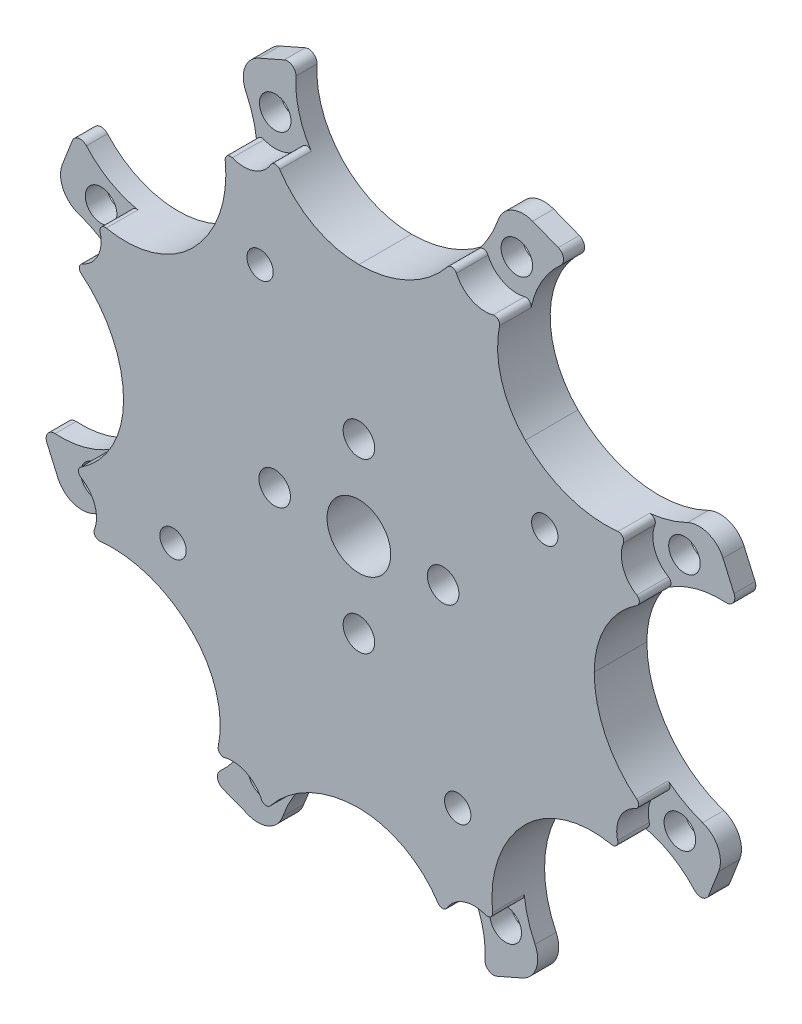
SolidWorks part; units mm, degrees
ref_plane "前视基准面" through (0, 0, 0) normal (0, 0, 1) x (1, 0, 0)
ref_plane "上视基准面" through (0, 0, 0) normal (0, 1, 0) x (1, 0, 0)
ref_plane "右视基准面" through (0, 0, 0) normal (1, 0, 0) x (0, 0, -1)
sketch "草图1" plane through (0, 0, 0) normal (0, 0, 1) x (1, 0, 0)
  line L0 (0, 31.3575) -> (0, 0) construction
  line L1 (0, 0) -> (22.1731, 22.1731) construction
  line L4 (0, 31.3575) -> (22.1731, 22.1731) construction
  line L6 (11.6409, 26.5357) -> (12.5976, 28.8454) construction
  line L7 (22.2808, 22.9688) -> (16.1797, 28.8872) construction
  line L8 (22.2808, 22.9688) -> (28.5472, 29.4288) construction
  line L9 (15.9368, 30.2296) -> (13.5034, 31.1755)
  line L10 (32.6446, 10.1066) -> (31.5928, 12.4961)
  line L11 (30.2296, -15.9368) -> (31.1755, -13.5034)
  line L12 (10.1066, -32.6446) -> (12.4961, -31.5928)
  line L13 (-15.9368, -30.2296) -> (-13.5034, -31.1755)
  line L14 (-32.6446, -10.1066) -> (-31.5928, -12.4961)
  line L15 (-30.2296, 15.9368) -> (-31.1755, 13.5034)
  line L16 (-10.1066, 32.6446) -> (-12.4961, 31.5928)
  circle A0 centre (0, 0) radius 31.3575 construction
  arc A9 (16.1797, 28.8872) -> (15.8091, 15.8091) centre (22.1731, 22.1731) ccw
  circle A13 centre (0, 0) radius 41 construction
  arc A16 (16.1797, 28.8872) -> (15.9368, 30.2296) centre (15.6469, 29.484) ccw
  arc A17 (13.5034, 31.1755) -> (10.2336, 29.6588) centre (12.5976, 28.8454) ccw
  arc A18 (0, 22.3575) -> (10.2336, 29.6588) centre (0, 33.18) ccw
  arc A19 (31.8671, 8.9856) -> (22.3575, 0) centre (31.3575, 0) ccw
  arc A20 (31.8671, 8.9856) -> (32.6446, 10.1066) centre (31.9124, 9.7843) ccw
  arc A21 (31.5928, 12.4961) -> (28.2082, 13.7357) centre (29.3046, 11.4889) ccw
  arc A22 (15.8091, 15.8091) -> (28.2082, 13.7357) centre (23.4618, 23.4618) ccw
  arc A24 (28.8872, -16.1797) -> (15.8091, -15.8091) centre (22.1731, -22.1731) ccw
  arc A25 (28.8872, -16.1797) -> (30.2296, -15.9368) centre (29.484, -15.6469) ccw
  arc A26 (31.1755, -13.5034) -> (29.6588, -10.2336) centre (28.8454, -12.5976) ccw
  arc A27 (22.3575, 0) -> (29.6588, -10.2336) centre (33.18, 0) ccw
  arc A29 (8.9856, -31.8671) -> (0, -22.3575) centre (0, -31.3575) ccw
  arc A30 (8.9856, -31.8671) -> (10.1066, -32.6446) centre (9.7843, -31.9124) ccw
  arc A31 (12.4961, -31.5928) -> (13.7357, -28.2082) centre (11.4889, -29.3046) ccw
  arc A32 (15.8091, -15.8091) -> (13.7357, -28.2082) centre (23.4618, -23.4618) ccw
  arc A34 (-16.1797, -28.8872) -> (-15.8091, -15.8091) centre (-22.1731, -22.1731) ccw
  arc A35 (-16.1797, -28.8872) -> (-15.9368, -30.2296) centre (-15.6469, -29.484) ccw
  arc A36 (-13.5034, -31.1755) -> (-10.2336, -29.6588) centre (-12.5976, -28.8454) ccw
  arc A37 (0, -22.3575) -> (-10.2336, -29.6588) centre (0, -33.18) ccw
  arc A39 (-31.8671, -8.9856) -> (-22.3575, 0) centre (-31.3575, 0) ccw
  arc A40 (-31.8671, -8.9856) -> (-32.6446, -10.1066) centre (-31.9124, -9.7843) ccw
  arc A41 (-31.5928, -12.4961) -> (-28.2082, -13.7357) centre (-29.3046, -11.4889) ccw
  arc A42 (-15.8091, -15.8091) -> (-28.2082, -13.7357) centre (-23.4618, -23.4618) ccw
  arc A44 (-28.8872, 16.1797) -> (-15.8091, 15.8091) centre (-22.1731, 22.1731) ccw
  arc A45 (-28.8872, 16.1797) -> (-30.2296, 15.9368) centre (-29.484, 15.6469) ccw
  arc A46 (-31.1755, 13.5034) -> (-29.6588, 10.2336) centre (-28.8454, 12.5976) ccw
  arc A47 (-22.3575, 0) -> (-29.6588, 10.2336) centre (-33.18, 0) ccw
  arc A49 (-8.9856, 31.8671) -> (0, 22.3575) centre (0, 31.3575) ccw
  arc A50 (-8.9856, 31.8671) -> (-10.1066, 32.6446) centre (-9.7843, 31.9124) ccw
  arc A51 (-12.4961, 31.5928) -> (-13.7357, 28.2082) centre (-11.4889, 29.3046) ccw
  arc A52 (-15.8091, 15.8091) -> (-13.7357, 28.2082) centre (-23.4618, 23.4618) ccw
  circle A54 centre (0, 0) radius 3.025
  circle A55 centre (0, 0) radius 8 construction
  circle A56 centre (-8, 0) radius 1.5
  circle A57 centre (0, 8) radius 1.5
  circle A58 centre (8, 0) radius 1.5
  circle A59 centre (0, -8) radius 1.5
  point P98 (0, 0)
  point P102 (0, 0)
  dimension "D1" = 9
  dimension "D3" = 45
  dimension "D5" = 9
  dimension "D8" = 82
  dimension "D9" = 9
  dimension "D10" = 2.5
  dimension "D11" = 0.8
  dimension "D13" = 6.05
  dimension "D14" = 16
  dimension "D15" = 3
  dimension "D2" = 24
  dimension "D6" = 11.4
  dimension "D7" = 2.5
  dimension "D17" = 8.5
  dimension "D12" = 8
  dimension "D16" = 4
extrude "凸台-拉伸1" add sketch "草图1" along normal blind 5
sketch "草图2" plane through (0, 0, 5) normal (0, 0, 1) x (1, 0, 0)
  line L0 (0, 0) -> (-22.3575, 0) construction
  line L1 (-9.3894, 17.659) -> (0, 0) construction
  circle A0 centre (0, 0) radius 20 construction
  circle A1 centre (-17.659, -9.3894) radius 1.25
  arc A2 (-22.3575, 0) -> (-26.3818, 8.4208) centre (-33.18, 0) ccw construction
  circle A3 centre (-9.3894, 17.659) radius 1.25
  circle A4 centre (17.659, 9.3894) radius 1.25
  circle A5 centre (9.3894, -17.659) radius 1.25
  point P3 (-17.659, -9.3894)
  point P13 (-9.3894, 17.659)
  point P15 (17.659, 9.3894)
  point P17 (9.3894, -17.659)
  point P19 (0, 0)
  dimension "D1" = 40
  dimension "D2" = 2.5
  dimension "D4" = 62
  dimension "D3" = 4
sketch "草图3" plane through (0, 0, 5) normal (0, 0, 1) x (1, 0, 0)
  line L0 (0, 0) -> (-11.4889, 29.3046) construction
  line L1 (0, 0) -> (-22.3575, 0) construction
  arc A2 (-12.4961, 31.5928) -> (-13.7357, 28.2082) centre (-11.4889, 29.3046) ccw construction
  arc A3 (-12.4961, 31.5928) -> (-13.7357, 28.2082) centre (-11.4889, 29.3046) ccw construction
  circle A4 centre (0, 0) radius 30 construction
  circle A5 centre (-10.9501, 27.9302) radius 1.5
  circle A6 centre (12.0067, 27.4925) radius 1.5
  circle A7 centre (27.9302, 10.9501) radius 1.5
  circle A8 centre (27.4925, -12.0067) radius 1.5
  circle A9 centre (10.9501, -27.9302) radius 1.5
  circle A10 centre (-12.0067, -27.4925) radius 1.5
  circle A11 centre (-27.9302, -10.9501) radius 1.5
  circle A12 centre (-27.4925, 12.0067) radius 1.5
  point P27 (0, 0)
  dimension "D1" = 60
  dimension "D2" = 3
  dimension "D3" = 8
extrude "切除-拉伸3" cut sketch "草图3" against normal blind 10
sketch "草图5" plane through (0, 0, 5) normal (0, 0, 1) x (1, 0, 0)
  line L2 (15.9368, 30.2296) -> (13.5034, 31.1755) construction
  line L3 (15.9368, 30.2296) -> (13.5034, 31.1755)
  line L4 (32.6446, 10.1066) -> (31.5928, 12.4961)
  line L5 (30.2296, -15.9368) -> (31.1755, -13.5034)
  line L6 (10.1066, -32.6446) -> (12.4961, -31.5928)
  line L7 (-15.9368, -30.2296) -> (-13.5034, -31.1755)
  line L8 (-32.6446, -10.1066) -> (-31.5928, -12.4961)
  line L9 (-30.2296, 15.9368) -> (-31.1755, 13.5034)
  line L10 (-10.1066, 32.6446) -> (-12.4961, 31.5928)
  arc A0 (9.0209, 27.201) -> (13.6156, 24.9604) centre (12.0067, 27.4925) ccw
  arc A16 (16.1797, 28.8872) -> (15.8091, 15.8091) centre (22.1731, 22.1731) ccw construction
  arc A17 (16.1797, 28.8872) -> (15.9368, 30.2296) centre (15.6469, 29.484) ccw construction
  arc A18 (13.5034, 31.1755) -> (10.2336, 29.6588) centre (12.5976, 28.8454) ccw construction
  arc A19 (0, 22.3575) -> (10.2336, 29.6588) centre (0, 33.18) ccw construction
  arc A20 (16.1797, 28.8872) -> (13.6156, 24.9604) centre (22.1731, 22.1731) ccw
  arc A21 (16.1797, 28.8872) -> (15.9368, 30.2296) centre (15.6469, 29.484) ccw
  arc A22 (13.5034, 31.1755) -> (10.2336, 29.6588) centre (12.5976, 28.8454) ccw
  arc A23 (9.0209, 27.201) -> (10.2336, 29.6588) centre (0, 33.18) ccw
  arc A24 (25.6128, 12.8552) -> (27.2773, 8.022) centre (27.9302, 10.9501) ccw
  arc A25 (31.8671, 8.9856) -> (27.2773, 8.022) centre (31.3575, 0) ccw
  arc A26 (31.8671, 8.9856) -> (32.6446, 10.1066) centre (31.9124, 9.7843) ccw
  arc A27 (31.5928, 12.4961) -> (28.2082, 13.7357) centre (29.3046, 11.4889) ccw
  arc A28 (25.6128, 12.8552) -> (28.2082, 13.7357) centre (23.4618, 23.4618) ccw
  arc A29 (27.201, -9.0209) -> (24.9604, -13.6156) centre (27.4925, -12.0067) ccw
  arc A30 (28.8872, -16.1797) -> (24.9604, -13.6156) centre (22.1731, -22.1731) ccw
  arc A31 (28.8872, -16.1797) -> (30.2296, -15.9368) centre (29.484, -15.6469) ccw
  arc A32 (31.1755, -13.5034) -> (29.6588, -10.2336) centre (28.8454, -12.5976) ccw
  arc A33 (27.201, -9.0209) -> (29.6588, -10.2336) centre (33.18, 0) ccw
  arc A34 (12.8552, -25.6128) -> (8.022, -27.2773) centre (10.9501, -27.9302) ccw
  arc A35 (8.9856, -31.8671) -> (8.022, -27.2773) centre (0, -31.3575) ccw
  arc A36 (8.9856, -31.8671) -> (10.1066, -32.6446) centre (9.7843, -31.9124) ccw
  arc A37 (12.4961, -31.5928) -> (13.7357, -28.2082) centre (11.4889, -29.3046) ccw
  arc A38 (12.8552, -25.6128) -> (13.7357, -28.2082) centre (23.4618, -23.4618) ccw
  arc A39 (-9.0209, -27.201) -> (-13.6156, -24.9604) centre (-12.0067, -27.4925) ccw
  arc A40 (-16.1797, -28.8872) -> (-13.6156, -24.9604) centre (-22.1731, -22.1731) ccw
  arc A41 (-16.1797, -28.8872) -> (-15.9368, -30.2296) centre (-15.6469, -29.484) ccw
  arc A42 (-13.5034, -31.1755) -> (-10.2336, -29.6588) centre (-12.5976, -28.8454) ccw
  arc A43 (-9.0209, -27.201) -> (-10.2336, -29.6588) centre (0, -33.18) ccw
  arc A44 (-25.6128, -12.8552) -> (-27.2773, -8.022) centre (-27.9302, -10.9501) ccw
  arc A45 (-31.8671, -8.9856) -> (-27.2773, -8.022) centre (-31.3575, 0) ccw
  arc A46 (-31.8671, -8.9856) -> (-32.6446, -10.1066) centre (-31.9124, -9.7843) ccw
  arc A47 (-31.5928, -12.4961) -> (-28.2082, -13.7357) centre (-29.3046, -11.4889) ccw
  arc A48 (-25.6128, -12.8552) -> (-28.2082, -13.7357) centre (-23.4618, -23.4618) ccw
  arc A49 (-27.201, 9.0209) -> (-24.9604, 13.6156) centre (-27.4925, 12.0067) ccw
  arc A50 (-28.8872, 16.1797) -> (-24.9604, 13.6156) centre (-22.1731, 22.1731) ccw
  arc A51 (-28.8872, 16.1797) -> (-30.2296, 15.9368) centre (-29.484, 15.6469) ccw
  arc A52 (-31.1755, 13.5034) -> (-29.6588, 10.2336) centre (-28.8454, 12.5976) ccw
  arc A53 (-27.201, 9.0209) -> (-29.6588, 10.2336) centre (-33.18, 0) ccw
  arc A54 (-12.8552, 25.6128) -> (-8.022, 27.2773) centre (-10.9501, 27.9302) ccw
  arc A55 (-8.9856, 31.8671) -> (-8.022, 27.2773) centre (0, 31.3575) ccw
  arc A56 (-8.9856, 31.8671) -> (-10.1066, 32.6446) centre (-9.7843, 31.9124) ccw
  arc A57 (-12.4961, 31.5928) -> (-13.7357, 28.2082) centre (-11.4889, 29.3046) ccw
  arc A58 (-12.8552, 25.6128) -> (-13.7357, 28.2082) centre (-23.4618, 23.4618) ccw
  point P20 (0, 0)
  point P96 (0, 0)
  dimension "D1" = 6
  dimension "D2" = 8
extrude "切除-拉伸5" cut sketch "草图5" against normal blind 3
fillet "圆角1" radius 0.5 16 edges at (27.2773, 8.022, 3.5) (27.201, -9.0209, 3.5) (24.9604, -13.6156, 3.5) (12.8552, -25.6128, 3.5) (8.022, -27.2773, 3.5) (-13.6156, -24.9604, 3.5) (-25.6128, -12.8552, 3.5) (-27.2773, -8.022, 3.5) (-27.201, 9.0209, 3.5) (-24.9604, 13.6156, 3.5) (-12.8552, 25.6128, 3.5) (-8.022, 27.2773, 3.5) (9.0209, 27.201, 3.5) (13.6156, 24.9604, 3.5) (25.6128, 12.8552, 3.5) (-9.0209, -27.201, 3.5)
hole_wizard "M3 螺纹孔1" positions "草图2" profile "草图8" tap size "M3" standard "GB" end condition through all
sketch "草图8" plane through (0, 0, 5) normal (1, 0, 0) x (0, -1, 0)
  line L0 (0, 0) -> (0, 5)
  line L1 (0, 5) -> (1.25, 5)
  line L2 (1.25, 5) -> (1.25, 0)
  line L5 (1.25, 0) -> (0, 0)
  line L11 (0, -6.35) -> (0, 107.95) construction
  dimension "通孔螺纹孔钻头直径" = 2.5
  dimension "通孔螺纹孔钻头深度" = 5
cosmetic thread "孔螺纹线1" parameters "D2"=3
cosmetic thread "孔螺纹线2" parameters "D2"=3
cosmetic thread "孔螺纹线3" parameters "D2"=3
cosmetic thread "孔螺纹线4" parameters "D2"=3
